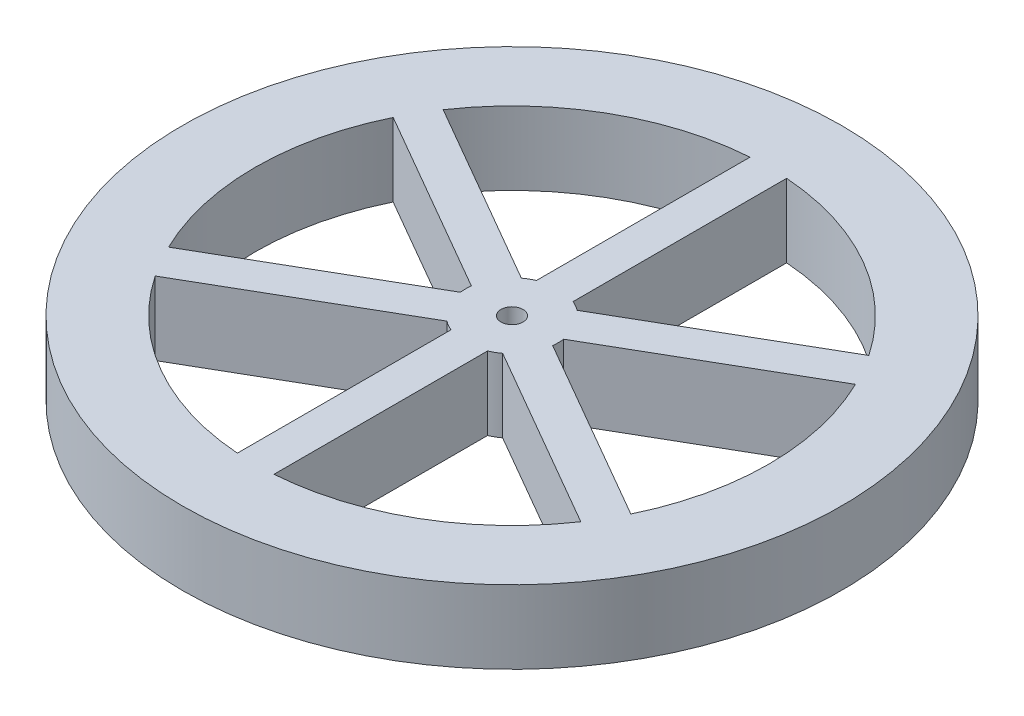
SolidWorks part; units mm, degrees
material "PBT General Purpose"
ref_plane "Front Plane" through (0, 0, 0) normal (0, 0, 1) x (1, 0, 0)
ref_plane "Top Plane" through (0, 0, 0) normal (0, 1, 0) x (1, 0, 0)
ref_plane "Right Plane" through (0, 0, 0) normal (1, 0, 0) x (0, 0, -1)
sketch "Sketch1" plane through (0, 0, 0) normal (0, 1, 0) x (1, 0, 0)
  line L0 (0, 35) -> (0, 45) construction
  line L2 (0, 6.35) -> (0, 35) construction
  line L3 (-2.5, 5.8372) -> (-2.5, 35)
  line L4 (2.5, 5.8372) -> (2.5, 35)
  line L5 (-2.5, 20.4186) -> (2.5, 20.4186) construction
  line L6 (5.4993, 3.175) -> (30.3109, 17.5) construction
  line L7 (6.3051, 0.7535) -> (31.5609, 15.3349)
  line L8 (3.8051, 5.0836) -> (29.0609, 19.6651)
  line L9 (5.4993, -3.175) -> (30.3109, -17.5) construction
  line L10 (3.8051, -5.0836) -> (29.0609, -19.6651)
  line L11 (6.3051, -0.7535) -> (31.5609, -15.3349)
  line L12 (0, -6.35) -> (0, -35) construction
  line L13 (-2.5, -5.8372) -> (-2.5, -35)
  line L14 (2.5, -5.8372) -> (2.5, -35)
  line L15 (-5.4993, -3.175) -> (-30.3109, -17.5) construction
  line L16 (-6.3051, -0.7535) -> (-31.5609, -15.3349)
  line L17 (-3.8051, -5.0836) -> (-29.0609, -19.6651)
  line L18 (-5.4993, 3.175) -> (-30.3109, 17.5) construction
  line L19 (-3.8051, 5.0836) -> (-29.0609, 19.6651)
  line L20 (-6.3051, 0.7535) -> (-31.5609, 15.3349)
  line L21 (-2.5, 35) -> (2.5, 35) construction
  circle A0 centre (0, 0) radius 45
  circle A1 centre (0, 0) radius 1.5
  arc A2 (-31.5609, 15.3349) -> (-31.5609, -15.3349) centre (0, 0) ccw
  arc A3 (-6.3051, 0.7535) -> (-6.3051, -0.7535) centre (0, 0) ccw
  arc A4 (-2.5, 35) -> (-29.0609, 19.6651) centre (0, 0) ccw
  arc A5 (-29.0609, -19.6651) -> (-2.5, -35) centre (0, 0) ccw
  arc A6 (2.5, -35) -> (29.0609, -19.6651) centre (0, 0) ccw
  arc A7 (31.5609, -15.3349) -> (31.5609, 15.3349) centre (0, 0) ccw
  arc A8 (29.0609, 19.6651) -> (2.5, 35) centre (0, 0) ccw
  arc A9 (-3.8051, -5.0836) -> (-2.5, -5.8372) centre (0, 0) ccw
  arc A10 (2.5, -5.8372) -> (3.8051, -5.0836) centre (0, 0) ccw
  arc A11 (6.3051, -0.7535) -> (6.3051, 0.7535) centre (0, 0) ccw
  arc A12 (3.8051, 5.0836) -> (2.5, 5.8372) centre (0, 0) ccw
  arc A13 (-2.5, 5.8372) -> (-3.8051, 5.0836) centre (0, 0) ccw
  point P4 (0, 0)
  point P7 (-2.5, 22.347)
  point P48 (0, 0)
  dimension "D1" = 90
  dimension "D2" = 3
  dimension "D4" = 6.35
  dimension "D3" = 10
  dimension "D5" = 5
  dimension "D6" = 6
extrude "Boss-Extrude1" add sketch "Sketch1" along normal blind 10
